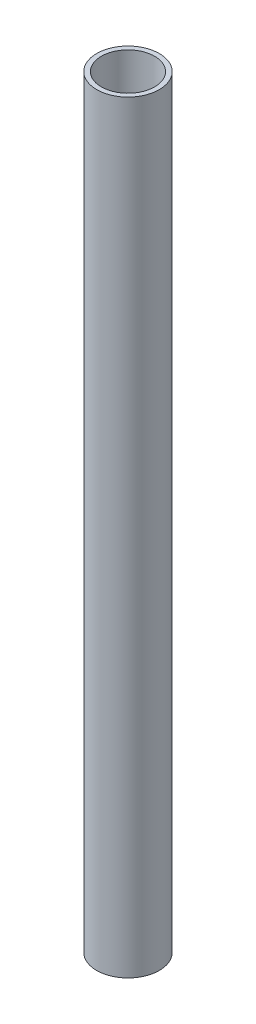
SolidWorks part; units mm, degrees
ref_plane "前视基准面" through (0, 0, 0) normal (0, 0, 1) x (1, 0, 0)
ref_plane "上视基准面" through (0, 0, 0) normal (0, 1, 0) x (1, 0, 0)
ref_plane "右视基准面" through (0, 0, 0) normal (1, 0, 0) x (0, 0, -1)
other "Configuration Table"
sketch "草图1" plane through (0, 0, 0) normal (0, 1, 0) x (1, 0, 0)
  circle A14 centre (0, 0) radius 16
  circle A15 centre (0, 0) radius 13.6
  dimension "D1" = 32
  dimension "D2" = 2.4
extrude "凸台-拉伸1" add sketch "草图1" along normal blind 390
